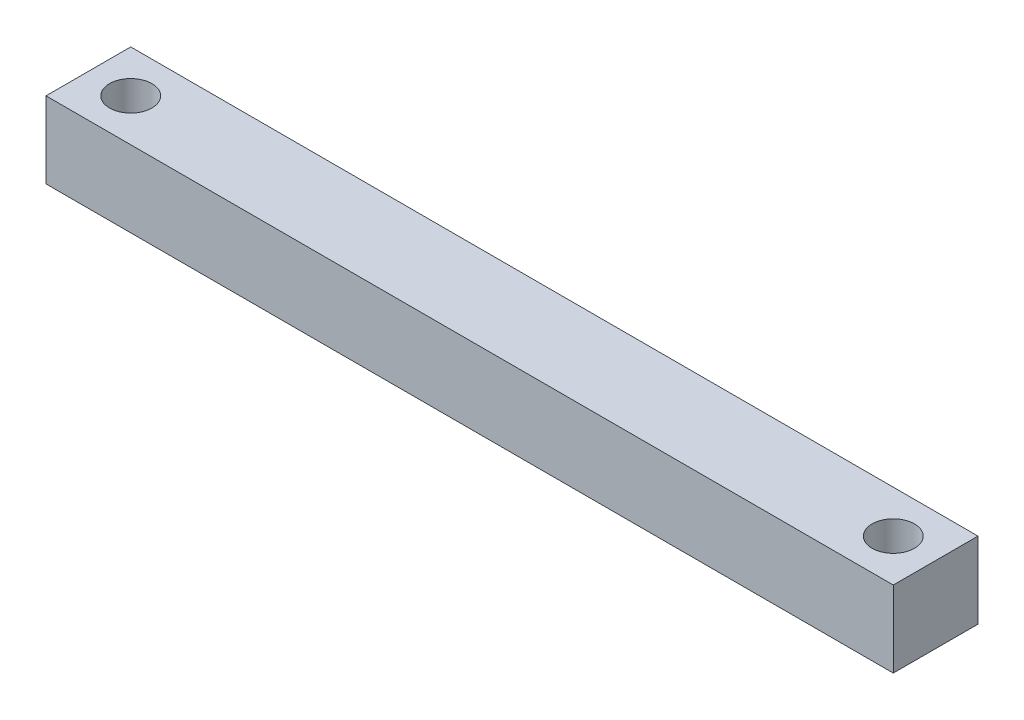
SolidWorks part; units mm, degrees
ref_plane "Front Plane" through (0, 0, 0) normal (0, 0, 1) x (1, 0, 0)
ref_plane "Top Plane" through (0, 0, 0) normal (0, 1, 0) x (1, 0, 0)
ref_plane "Right Plane" through (0, 0, 0) normal (1, 0, 0) x (0, 0, -1)
sketch " v  " plane through (0, 0, 0) normal (0, 1, 0) x (1, 0, 0)
  line L0 (0, -5) -> (0, 5) construction
  line L1 (-50, 5) -> (50, 5)
  line L2 (-50, 5) -> (-50, -5)
  line L3 (-50, -5) -> (50, -5)
  line L4 (50, 5) -> (50, -5)
  point P4 (0, 5)
  point P7 (50, 0)
  dimension "D1" = 100
  dimension "D2" = 10
extrude "Boss-Extrude1" add sketch " v  " along normal blind 9.0049
sketch "Sketch2" plane through (0, 9.0049, 0) normal (0, 1, 0) x (1, 0, 0)
  line L0 (-45, 2.5) -> (-45, 5) construction
  line L1 (50, 5) -> (-50, 5) construction
  line L2 (-45, -2.5) -> (-45, -5) construction
  line L3 (-50, -5) -> (50, -5) construction
  line L4 (-47.5, 0) -> (-50, 0) construction
  line L5 (-50, 5) -> (-50, -5) construction
  line L6 (45, 2.5) -> (45, 5) construction
  line L7 (47.5, 0) -> (50, 0) construction
  line L8 (50, -5) -> (50, 5) construction
  line L9 (45, -2.5) -> (45, -5) construction
  circle A0 centre (-45, 0) radius 2.5
  circle A1 centre (45, 0) radius 2.5
  dimension "D1" = 5
extrude "Cut-Extrude1" cut sketch "Sketch2" against normal through all
